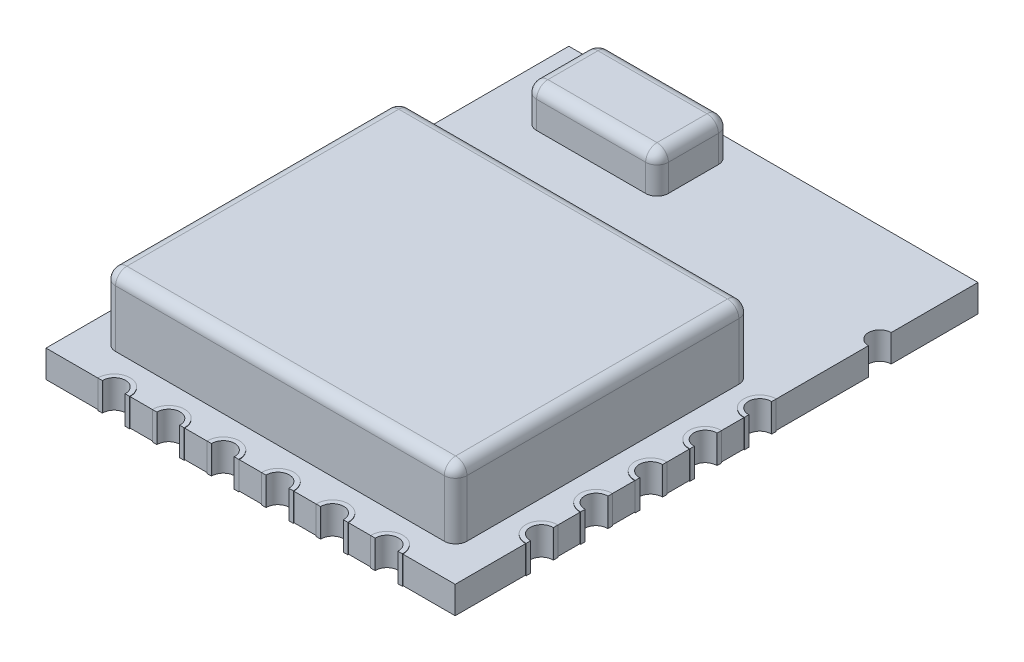
SolidWorks part; units mm, degrees
ref_plane "Front Plane" through (0, 0, 0) normal (0, 0, 1) x (1, 0, 0)
ref_plane "Top Plane" through (0, 0, 0) normal (0, 1, 0) x (1, 0, 0)
ref_plane "Right Plane" through (0, 0, 0) normal (1, 0, 0) x (0, 0, -1)
sketch "Sketch2" plane through (0, 0, 0) normal (0, 1, 0) x (1, 0, 0)
  line L0 (-4.5, -5.75) -> (-4.5, -4.1)
  line L3 (-4.5, 5.75) -> (4.5, 5.75)
  line L4 (4.5, -5.75) -> (4.5, -4.1)
  line L5 (-4.5, -5.75) -> (4.5, 5.75) construction
  line L6 (-4.5, 5.75) -> (4.5, -5.75) construction
  line L7 (0, -5.75) -> (0, 5.75) construction
  line L8 (-4.5, 1.2) -> (-4.5, 5.75)
  line L9 (-4.5, 0) -> (-4.5, 0.7)
  line L10 (-4.5, -1.2) -> (-4.5, -0.5)
  line L11 (-4.5, -2.4) -> (-4.5, -1.7)
  line L12 (-4.5, -2.9) -> (-4.5, -3.6)
  line L13 (4.5, 1.2) -> (4.5, 3.34)
  line L14 (4.5, 0) -> (4.5, 0.7)
  line L15 (4.5, -1.2) -> (4.5, -0.5)
  line L16 (4.5, -2.4) -> (4.5, -1.7)
  line L17 (4.5, -3.6) -> (4.5, -2.9)
  line L18 (-4.5, -5.75) -> (-3.25, -5.75)
  line L19 (-2.75, -5.75) -> (-2.05, -5.75)
  line L20 (-1.55, -5.75) -> (-0.85, -5.75)
  line L21 (-0.35, -5.75) -> (0.35, -5.75)
  line L22 (0.85, -5.75) -> (1.55, -5.75)
  line L23 (2.05, -5.75) -> (2.75, -5.75)
  line L24 (3.25, -5.75) -> (4.5, -5.75)
  line L25 (4.5, 3.84) -> (4.5, 5.75)
  arc A0 (-4.5, -4.1) -> (-4.5, -3.6) centre (-4.5, -3.85) ccw
  arc A1 (-4.5, -2.9) -> (-4.5, -2.4) centre (-4.5, -2.65) ccw
  arc A2 (-4.5, -1.7) -> (-4.5, -1.2) centre (-4.5, -1.45) ccw
  arc A3 (-4.5, -0.5) -> (-4.5, 0) centre (-4.5, -0.25) ccw
  arc A4 (-4.5, 0.7) -> (-4.5, 1.2) centre (-4.5, 0.95) ccw
  arc A5 (4.5, -4.1) -> (4.5, -3.6) centre (4.5, -3.85) cw
  arc A6 (4.5, -2.9) -> (4.5, -2.4) centre (4.5, -2.65) cw
  arc A7 (4.5, -1.7) -> (4.5, -1.2) centre (4.5, -1.45) cw
  arc A8 (4.5, -0.5) -> (4.5, 0) centre (4.5, -0.25) cw
  arc A9 (4.5, 0.7) -> (4.5, 1.2) centre (4.5, 0.95) cw
  arc A10 (-2.75, -5.75) -> (-3.25, -5.75) centre (-3, -5.75) ccw
  arc A11 (-1.55, -5.75) -> (-2.05, -5.75) centre (-1.8, -5.75) ccw
  arc A12 (-0.35, -5.75) -> (-0.85, -5.75) centre (-0.6, -5.75) ccw
  arc A13 (0.85, -5.75) -> (0.35, -5.75) centre (0.6, -5.75) ccw
  arc A14 (2.05, -5.75) -> (1.55, -5.75) centre (1.8, -5.75) ccw
  arc A15 (3.25, -5.75) -> (2.75, -5.75) centre (3, -5.75) ccw
  arc A16 (4.5, 3.84) -> (4.5, 3.34) centre (4.5, 3.59) ccw
  point P0 (0, 0)
  dimension "D1" = 0.25
  dimension "D2" = 4.5
  dimension "D3" = 0.95
  dimension "D4" = 3.59
  dimension "D5" = 5.75
extrude "Boss-Extrude1" add sketch "Sketch2" along normal blind 0.6 contours L3 L25 A16 L13 A9 L14 A8 L15 A7 L16 A6 L17 A5 L4 L24 A15 L23 A14 L22 A13 L21 A12 L20 A11 L19 A10 L18 L0 A0 L12 A1 L11 A2 L10 A3 L9 A4 L8
sketch "Sketch3" plane through (0, 0.6, 0) normal (0, 1, 0) x (1, 0, 0)
  line L0 (-4.5, 1.2) -> (-4.5, 5.75) construction
  line L2 (-3.92, -5.05) -> (3.81, -5.05)
  line L5 (-3.92, 1.43) -> (-3.92, -5.05)
  line L7 (3.81, 1.43) -> (3.81, -5.05)
  line L9 (3.81, 1.43) -> (-3.92, 1.43)
  dimension "D1" = 0.58
  dimension "D2" = 8.31
  dimension "D3" = 4.32
  dimension "D4" = 10.8
extrude "Boss-Extrude2" add sketch "Sketch3" along normal blind 1.5 contours L9 L5 L2 L7
fillet "Fillet1" radius 0.25 8 edges at (-0.055, 2.1, 5.05) (-3.92, 2.1, 1.81) (-0.055, 2.1, -1.43) (3.81, 2.1, 1.81) (3.81, 1.35, -1.43) (3.81, 1.35, 5.05) (-3.92, 1.35, 5.05) (-3.92, 1.35, -1.43)
sketch "Sketch4" plane through (0, 0.6, 0) normal (0, 1, 0) x (1, 0, 0)
  line L0 (-4.5, 1.2) -> (-4.5, 5.75) construction
  line L2 (-3.67, -5.05) -> (3.56, -5.05) construction
  line L3 (-3.5, 5.39) -> (-0.6, 5.39)
  line L5 (-3.5, 5.39) -> (-3.5, 3.79)
  line L6 (-3.5, 3.79) -> (-0.6, 3.79)
  line L7 (-0.6, 5.39) -> (-0.6, 3.79)
  dimension "D1" = 2.9
  dimension "D2" = 1.6
  dimension "D3" = 1
  dimension "D4" = 8.84
extrude "Boss-Extrude3" add sketch "Sketch4" along normal blind 0.8438 contours L3 L7 L6 L5
fillet "Fillet2" radius 0.25 8 edges at (-3.5, 1.0219, -5.39) (-3.5, 1.0219, -3.79) (-0.6, 1.0219, -5.39) (-0.6, 1.0219, -3.79) (-3.5, 1.4438, -4.59) (-2.05, 1.4438, -5.39) (-0.6, 1.4438, -4.59) (-2.05, 1.4438, -3.79)
sketch "Sketch6" plane through (0, 0, 0) normal (0, -1, 0) x (1, 0, 0)
  line L0 (-4.5, 4.2) -> (-4.5, 4.1)
  line L1 (-3.35, 5.75) -> (-3.25, 5.75)
  line L2 (4.5, 4.2) -> (4.5, 4.1)
  line L3 (-4.5, -0.6) -> (-4.5, -0.7)
  line L4 (-4.5, 0.6) -> (-4.5, 0.5)
  line L5 (-4.5, 1.8) -> (-4.5, 1.7)
  line L6 (-4.5, 3) -> (-4.5, 2.9)
  line L7 (-4.5, 3.6) -> (-4.5, 3.5)
  line L8 (-4.5, 2.4) -> (-4.5, 2.3)
  line L9 (-4.5, 1.2) -> (-4.5, 1.1)
  line L10 (-4.5, 0) -> (-4.5, -0.1)
  line L11 (-4.5, -1.2) -> (-4.5, -1.3)
  line L12 (-2.75, 5.75) -> (-2.65, 5.75)
  line L13 (-1.55, 5.75) -> (-1.45, 5.75)
  line L14 (-0.35, 5.75) -> (-0.25, 5.75)
  line L15 (0.85, 5.75) -> (0.95, 5.75)
  line L16 (2.05, 5.75) -> (2.15, 5.75)
  line L17 (3.25, 5.75) -> (3.35, 5.75)
  line L18 (4.5, 3.6) -> (4.5, 3.5)
  line L19 (4.5, 2.4) -> (4.5, 2.3)
  line L20 (4.5, 1.2) -> (4.5, 1.1)
  line L21 (4.5, 0) -> (4.5, -0.1)
  line L22 (4.5, -1.2) -> (4.5, -1.3)
  line L23 (4.5, -0.6) -> (4.5, -0.7)
  line L24 (4.5, 0.6) -> (4.5, 0.5)
  line L25 (4.5, 1.8) -> (4.5, 1.7)
  line L26 (4.5, 3) -> (4.5, 2.9)
  line L27 (2.65, 5.75) -> (2.75, 5.75)
  line L28 (1.45, 5.75) -> (1.55, 5.75)
  line L29 (0.25, 5.75) -> (0.35, 5.75)
  line L30 (-0.95, 5.75) -> (-0.85, 5.75)
  line L31 (-2.15, 5.75) -> (-2.05, 5.75)
  line L32 (-4.5, -1.2) -> (-4.5, -5.75) construction
  line L33 (-4.5, -5.75) -> (4.5, -5.75) construction
  arc A0 (-4.5, 3.5) -> (-4.5, 4.2) centre (-4.5, 3.85) ccw
  arc A1 (-4.5, 2.3) -> (-4.5, 3) centre (-4.5, 2.65) ccw
  arc A2 (-4.5, 1.1) -> (-4.5, 1.8) centre (-4.5, 1.45) ccw
  arc A3 (-4.5, -0.1) -> (-4.5, 0.6) centre (-4.5, 0.25) ccw
  arc A4 (-4.5, -1.3) -> (-4.5, -0.6) centre (-4.5, -0.95) ccw
  arc A5 (-3.35, 5.75) -> (-2.65, 5.75) centre (-3, 5.75) ccw
  arc A6 (-2.15, 5.75) -> (-1.45, 5.75) centre (-1.8, 5.75) ccw
  arc A7 (-0.95, 5.75) -> (-0.25, 5.75) centre (-0.6, 5.75) ccw
  arc A8 (0.25, 5.75) -> (0.95, 5.75) centre (0.6, 5.75) ccw
  arc A9 (1.45, 5.75) -> (2.15, 5.75) centre (1.8, 5.75) ccw
  arc A10 (2.65, 5.75) -> (3.35, 5.75) centre (3, 5.75) ccw
  arc A11 (4.5, 4.2) -> (4.5, 3.5) centre (4.5, 3.85) ccw
  arc A12 (4.5, 3) -> (4.5, 2.3) centre (4.5, 2.65) ccw
  arc A13 (4.5, 1.8) -> (4.5, 1.1) centre (4.5, 1.45) ccw
  arc A14 (4.5, 0.6) -> (4.5, -0.1) centre (4.5, 0.25) ccw
  arc A15 (4.5, -0.6) -> (4.5, -1.3) centre (4.5, -0.95) ccw
  arc A16 (4.5, -0.7) -> (4.5, -1.2) centre (4.5, -0.95) ccw
  arc A17 (-4.5, 3.6) -> (-4.5, 4.1) centre (-4.5, 3.85) ccw
  arc A18 (-4.5, 2.4) -> (-4.5, 2.9) centre (-4.5, 2.65) ccw
  arc A19 (-4.5, 1.2) -> (-4.5, 1.7) centre (-4.5, 1.45) ccw
  arc A20 (-4.5, 0) -> (-4.5, 0.5) centre (-4.5, 0.25) ccw
  arc A21 (-4.5, -1.2) -> (-4.5, -0.7) centre (-4.5, -0.95) ccw
  arc A22 (-3.25, 5.75) -> (-2.75, 5.75) centre (-3, 5.75) ccw
  arc A23 (-2.05, 5.75) -> (-1.55, 5.75) centre (-1.8, 5.75) ccw
  arc A24 (-0.85, 5.75) -> (-0.35, 5.75) centre (-0.6, 5.75) ccw
  arc A25 (0.35, 5.75) -> (0.85, 5.75) centre (0.6, 5.75) ccw
  arc A26 (1.55, 5.75) -> (2.05, 5.75) centre (1.8, 5.75) ccw
  arc A27 (2.75, 5.75) -> (3.25, 5.75) centre (3, 5.75) ccw
  arc A28 (4.5, 4.1) -> (4.5, 3.6) centre (4.5, 3.85) ccw
  arc A29 (4.5, 2.9) -> (4.5, 2.4) centre (4.5, 2.65) ccw
  arc A30 (4.5, 1.7) -> (4.5, 1.2) centre (4.5, 1.45) ccw
  arc A31 (4.5, 0.5) -> (4.5, 0) centre (4.5, 0.25) ccw
  line M10 (-4.5, -1.2) -> (-4.5, -5.75)
  line M14 (4.5, -3.34) -> (4.5, -1.2)
  arc M15 (4.5, -1.2) -> (4.5, -0.7) centre (4.5, -0.95) cw
  line M16 (4.5, -0.7) -> (4.5, 0)
  arc M17 (4.5, 0) -> (4.5, 0.5) centre (4.5, 0.25) cw
  line M18 (4.5, 0.5) -> (4.5, 1.2)
  arc M19 (4.5, 1.2) -> (4.5, 1.7) centre (4.5, 1.45) cw
  line M20 (4.5, 1.7) -> (4.5, 2.4)
  arc M21 (4.5, 2.4) -> (4.5, 2.9) centre (4.5, 2.65) cw
  line M22 (4.5, 2.9) -> (4.5, 3.6)
  arc M23 (4.5, 3.6) -> (4.5, 4.1) centre (4.5, 3.85) cw
  line M24 (4.5, 4.1) -> (4.5, 5.75)
  line M25 (4.5, 5.75) -> (3.25, 5.75)
  arc M26 (3.25, 5.75) -> (2.75, 5.75) centre (3, 5.75) cw
  line M27 (2.75, 5.75) -> (2.05, 5.75)
  arc M28 (2.05, 5.75) -> (1.55, 5.75) centre (1.8, 5.75) cw
  line M29 (1.55, 5.75) -> (0.85, 5.75)
  arc M30 (0.85, 5.75) -> (0.35, 5.75) centre (0.6, 5.75) cw
  line M31 (0.35, 5.75) -> (-0.35, 5.75)
  arc M32 (-0.35, 5.75) -> (-0.85, 5.75) centre (-0.6, 5.75) cw
  line M33 (-0.85, 5.75) -> (-1.55, 5.75)
  arc M34 (-1.55, 5.75) -> (-2.05, 5.75) centre (-1.8, 5.75) cw
  line M35 (-2.05, 5.75) -> (-2.75, 5.75)
  arc M36 (-2.75, 5.75) -> (-3.25, 5.75) centre (-3, 5.75) cw
  line M37 (-3.25, 5.75) -> (-4.5, 5.75)
  line M46 (-4.5, 0) -> (-4.5, -0.7)
  arc M47 (-4.5, -0.7) -> (-4.5, -1.2) centre (-4.5, -0.95) cw
  dimension "D1" = 0.35
  dimension "D2" = 0.25
  dimension "D3" = 1.5
  dimension "D4" = 2.7
  dimension "D5" = 3.9
  dimension "D6" = 5.1
  dimension "D7" = 6.3
  dimension "D8" = 7.5
  dimension "D9" = 9
  dimension "D10" = 4.8
  dimension "D11" = 6
  dimension "D12" = 7.2
  dimension "D13" = 8.4
  dimension "D14" = 9.6
  dimension "D15" = 11.5
extrude "Boss-Extrude4" add sketch "Sketch6" against normal blind 0.61 and the other way blind 0.01 contours A4 M10 M46 M47 | A5 M37 M35 M36 | A6 M35 M33 M34 | A7 M33 M31 M32 | A8 M31 M29 M30 | A9 M29 M27 M28 | A10 M27 M25 M26 | A11 M24 M22 M23 | A12 M22 M20 M21 | A13 M20 M18 M19 | A14 M18 M16 M17 | A15 M16 M14 M15 | A17 L0 A0 L7 | A18 L6 A1 L8 | A2 L5 A19 L9 | A20 L4 A3 L10
sketch "Sketch7" plane through (0, 0, 0) normal (0, -1, 0) x (1, 0, 0)
  line L0 (-4.5, 2.3) -> (-3.5, 2.3)
  line L1 (-4.5, 3.5) -> (-3.5, 3.5)
  line L2 (-4.5, 3.5) -> (-4.5, 3.6)
  line L3 (-4.5, 4.2) -> (-3.5, 4.2)
  line L4 (-3.5, 3.5) -> (-3.5, 4.2)
  line L5 (-4.5, 3) -> (-3.5, 3)
  line L6 (-4.5, 2.3) -> (-4.5, 2.4)
  line L7 (-3.5, 2.3) -> (-3.5, 3)
  line L8 (-4.5, 1.1) -> (-3.5, 1.1)
  line L9 (-4.5, 1.8) -> (-3.5, 1.8)
  line L10 (-4.5, 1.1) -> (-4.5, 1.2)
  line L11 (-3.5, 1.1) -> (-3.5, 1.8)
  line L12 (-4.5, -0.1) -> (-3.5, -0.1)
  line L13 (-4.5, 0.6) -> (-3.5, 0.6)
  line L14 (-4.5, -0.1) -> (-4.5, 0)
  line L15 (-3.5, -0.1) -> (-3.5, 0.6)
  line L16 (-4.5, -1.3) -> (-3.5, -1.3)
  line L17 (-4.5, -0.6) -> (-3.5, -0.6)
  line L18 (-4.5, -1.3) -> (-4.5, -1.2)
  line L19 (-3.5, -1.3) -> (-3.5, -0.6)
  line L20 (-4.5, 4.1) -> (-4.5, 4.2)
  line L23 (3.5, -1.3) -> (3.5, -0.6)
  line L24 (4.5, -1.3) -> (4.5, -1.2)
  line L25 (4.5, -0.6) -> (3.5, -0.6)
  line L26 (4.5, -1.3) -> (3.5, -1.3)
  line L27 (3.5, -0.1) -> (3.5, 0.6)
  line L28 (4.5, -0.1) -> (4.5, 0)
  line L29 (4.5, 0.6) -> (3.5, 0.6)
  line L30 (4.5, -0.1) -> (3.5, -0.1)
  line L31 (3.5, 1.1) -> (3.5, 1.8)
  line L32 (4.5, 1.1) -> (4.5, 1.2)
  line L33 (4.5, 1.8) -> (3.5, 1.8)
  line L34 (4.5, 1.1) -> (3.5, 1.1)
  line L35 (3.5, 2.3) -> (3.5, 3)
  line L36 (4.5, 2.3) -> (4.5, 2.4)
  line L37 (4.5, 3) -> (3.5, 3)
  line L38 (3.5, 3.5) -> (3.5, 4.2)
  line L39 (4.5, 4.2) -> (3.5, 4.2)
  line L40 (4.5, 3.5) -> (4.5, 3.6)
  line L41 (4.5, 3.5) -> (3.5, 3.5)
  line L42 (4.5, 2.3) -> (3.5, 2.3)
  line L43 (-2.15, 5.75) -> (-2.05, 5.75)
  line L44 (-3.35, 5.75) -> (-3.25, 5.75)
  line L45 (-3.35, 5.75) -> (-3.35, 4.75)
  line L46 (-3.35, 4.75) -> (-2.65, 4.75)
  line L47 (-2.65, 5.75) -> (-2.65, 4.75)
  line L48 (-2.15, 5.75) -> (-2.15, 4.75)
  line L49 (-2.15, 4.75) -> (-1.45, 4.75)
  line L50 (-1.45, 5.75) -> (-1.45, 4.75)
  line L51 (-0.95, 5.75) -> (-0.85, 5.75)
  line L52 (-0.95, 5.75) -> (-0.95, 4.75)
  line L53 (-0.95, 4.75) -> (-0.25, 4.75)
  line L54 (-0.25, 5.75) -> (-0.25, 4.75)
  line L55 (0.25, 5.75) -> (0.35, 5.75)
  line L56 (0.25, 5.75) -> (0.25, 4.75)
  line L57 (0.25, 4.75) -> (0.95, 4.75)
  line L58 (0.95, 5.75) -> (0.95, 4.75)
  line L59 (1.45, 5.75) -> (1.55, 5.75)
  line L60 (1.45, 5.75) -> (1.45, 4.75)
  line L61 (1.45, 4.75) -> (2.15, 4.75)
  line L62 (2.15, 5.75) -> (2.15, 4.75)
  line L63 (2.65, 5.75) -> (2.75, 5.75)
  line L64 (2.65, 5.75) -> (2.65, 4.75)
  line L65 (2.65, 4.75) -> (3.35, 4.75)
  line L66 (3.35, 5.75) -> (3.35, 4.75)
  line L67 (-4.5, 2.9) -> (-4.5, 3)
  line L68 (-4.5, 1.7) -> (-4.5, 1.8)
  line L69 (-4.5, 0.5) -> (-4.5, 0.6)
  line L70 (-4.5, -0.7) -> (-4.5, -0.6)
  line L71 (-2.75, 5.75) -> (-2.65, 5.75)
  line L72 (-1.55, 5.75) -> (-1.45, 5.75)
  line L73 (-0.35, 5.75) -> (-0.25, 5.75)
  line L74 (0.85, 5.75) -> (0.95, 5.75)
  line L75 (2.05, 5.75) -> (2.15, 5.75)
  line L76 (3.25, 5.75) -> (3.35, 5.75)
  line L77 (4.5, 4.1) -> (4.5, 4.2)
  line L78 (4.5, 2.9) -> (4.5, 3)
  line L79 (4.5, 1.7) -> (4.5, 1.8)
  line L80 (4.5, 0.5) -> (4.5, 0.6)
  line L81 (4.5, -0.7) -> (4.5, -0.6)
  line L82 (-4.5, 5.75) -> (-4.5, 4.2) construction
  line L83 (-4.5, 5.75) -> (-3.35, 5.75) construction
  arc A0 (-3.25, 5.75) -> (-2.75, 5.75) centre (-3, 5.75) ccw
  arc A1 (-2.05, 5.75) -> (-1.55, 5.75) centre (-1.8, 5.75) ccw
  arc A2 (-0.85, 5.75) -> (-0.35, 5.75) centre (-0.6, 5.75) ccw
  arc A3 (0.35, 5.75) -> (0.85, 5.75) centre (0.6, 5.75) ccw
  arc A4 (1.55, 5.75) -> (2.05, 5.75) centre (1.8, 5.75) ccw
  arc A5 (2.75, 5.75) -> (3.25, 5.75) centre (3, 5.75) ccw
  arc A6 (-4.5, 3.6) -> (-4.5, 4.1) centre (-4.5, 3.85) ccw
  arc A7 (-4.5, 2.4) -> (-4.5, 2.9) centre (-4.5, 2.65) ccw
  arc A8 (-4.5, 1.2) -> (-4.5, 1.7) centre (-4.5, 1.45) ccw
  arc A9 (-4.5, 0) -> (-4.5, 0.5) centre (-4.5, 0.25) ccw
  arc A10 (-4.5, -1.2) -> (-4.5, -0.7) centre (-4.5, -0.95) ccw
  arc A11 (4.5, -0.7) -> (4.5, -1.2) centre (4.5, -0.95) ccw
  arc A12 (4.5, 0.5) -> (4.5, 0) centre (4.5, 0.25) ccw
  arc A13 (4.5, 1.7) -> (4.5, 1.2) centre (4.5, 1.45) ccw
  arc A14 (4.5, 2.9) -> (4.5, 2.4) centre (4.5, 2.65) ccw
  arc A15 (4.5, 4.1) -> (4.5, 3.6) centre (4.5, 3.85) ccw
  dimension "D1" = 1
extrude "Boss-Extrude5" add sketch "Sketch7" along normal blind 0.01 contours L46 L47 L71 A0 L44 L45
sketch "Sketch8" plane through (4.5, 0, 0) normal (1, 0, 0) x (0, 0, -1)
  line L0 (-3.6, 0.61) -> (-3.6, -0.01)
  line L1 (-4.2, 0.61) -> (-4.1, 0.61)
  line L2 (-4.2, 0.61) -> (-4.2, -0.01)
  line L3 (-4.2, -0.01) -> (-4.1, -0.01)
  line L4 (-4.1, 0.61) -> (-4.1, -0.01)
  line L5 (-3.6, 0.61) -> (-3.5, 0.61)
  line L6 (-3.6, -0.01) -> (-3.5, -0.01)
  line L7 (-3.5, 0.61) -> (-3.5, -0.01)
  line L8 (-3, 0.61) -> (-3, -0.01)
  line L9 (-3, 0.61) -> (-2.9, 0.61)
  line L10 (-3, -0.01) -> (-2.9, -0.01)
  line L11 (-2.9, 0.61) -> (-2.9, -0.01)
  line L12 (-2.4, 0.61) -> (-2.4, -0.01)
  line L13 (-2.4, 0.61) -> (-2.3, 0.61)
  line L14 (-2.4, -0.01) -> (-2.3, -0.01)
  line L15 (-2.3, 0.61) -> (-2.3, -0.01)
  line L16 (-1.8, 0.61) -> (-1.8, -0.01)
  line L17 (-1.8, 0.61) -> (-1.7, 0.61)
  line L18 (-1.8, -0.01) -> (-1.7, -0.01)
  line L19 (-1.7, 0.61) -> (-1.7, -0.01)
  line L20 (-1.2, 0.61) -> (-1.2, -0.01)
  line L21 (-1.2, 0.61) -> (-1.1, 0.61)
  line L22 (-1.2, -0.01) -> (-1.1, -0.01)
  line L23 (-1.1, 0.61) -> (-1.1, -0.01)
  line L24 (-0.6, 0.61) -> (-0.6, -0.01)
  line L25 (-0.6, 0.61) -> (-0.5, 0.61)
  line L26 (-0.6, -0.01) -> (-0.5, -0.01)
  line L27 (-0.5, 0.61) -> (-0.5, -0.01)
  line L28 (0, 0.61) -> (0, -0.01)
  line L29 (0, 0.61) -> (0.1, 0.61)
  line L30 (0, -0.01) -> (0.1, -0.01)
  line L31 (0.1, 0.61) -> (0.1, -0.01)
  line L32 (0.6, 0.61) -> (0.6, -0.01)
  line L33 (0.6, 0.61) -> (0.7, 0.61)
  line L34 (0.6, -0.01) -> (0.7, -0.01)
  line L35 (0.7, 0.61) -> (0.7, -0.01)
  line L36 (1.2, 0.61) -> (1.2, -0.01)
  line L37 (1.2, 0.61) -> (1.3, 0.61)
  line L38 (1.2, -0.01) -> (1.3, -0.01)
  line L39 (1.3, 0.61) -> (1.3, -0.01)
  line L40 (-4.1, 0.61) -> (-4.1, -0.01) construction
  line L41 (-4.1, 0.61) -> (-4.2, 0.61) construction
  dimension "D1" = 0.5
  dimension "D2" = 0.6
  dimension "D3" = 1.1
  dimension "D4" = 1.7
  dimension "D5" = 2.3
  dimension "D6" = 2.9
  dimension "D7" = 3.5
  dimension "D8" = 4.1
  dimension "D9" = 4.7
  dimension "D10" = 5.3
  dimension "D11" = 0.62
sketch "Sketch9" plane through (0, 0, 5.75) normal (0, 0, 1) x (1, 0, 0)
  line L0 (-2.65, 0.61) -> (-2.65, -0.01)
  line L1 (-3.35, 0.61) -> (-3.25, 0.61)
  line L2 (-3.35, 0.61) -> (-3.35, -0.01)
  line L3 (-3.35, -0.01) -> (-3.25, -0.01)
  line L4 (-3.25, 0.61) -> (-3.25, -0.01)
  line L5 (-2.75, 0.61) -> (-2.65, 0.61)
  line L6 (-2.75, -0.01) -> (-2.65, -0.01)
  line L7 (-2.75, 0.61) -> (-2.75, -0.01)
  line L8 (-2.05, 0.61) -> (-2.05, -0.01)
  line L9 (-2.15, 0.61) -> (-2.05, 0.61)
  line L10 (-2.15, -0.01) -> (-2.05, -0.01)
  line L11 (-2.15, 0.61) -> (-2.15, -0.01)
  line L12 (-1.45, 0.61) -> (-1.45, -0.01)
  line L13 (-1.55, 0.61) -> (-1.45, 0.61)
  line L14 (-1.55, -0.01) -> (-1.45, -0.01)
  line L15 (-1.55, 0.61) -> (-1.55, -0.01)
  line L16 (-0.85, 0.61) -> (-0.85, -0.01)
  line L17 (-0.95, 0.61) -> (-0.85, 0.61)
  line L18 (-0.95, -0.01) -> (-0.85, -0.01)
  line L19 (-0.95, 0.61) -> (-0.95, -0.01)
  line L20 (-0.25, 0.61) -> (-0.25, -0.01)
  line L21 (-0.35, 0.61) -> (-0.25, 0.61)
  line L22 (-0.35, -0.01) -> (-0.25, -0.01)
  line L23 (-0.35, 0.61) -> (-0.35, -0.01)
  line L24 (0.25, 0.61) -> (0.35, 0.61)
  line L25 (0.35, 0.61) -> (0.35, -0.01)
  line L26 (0.25, -0.01) -> (0.35, -0.01)
  line L27 (0.25, 0.61) -> (0.25, -0.01)
  line L28 (0.85, 0.61) -> (0.95, 0.61)
  line L29 (0.95, 0.61) -> (0.95, -0.01)
  line L30 (0.85, -0.01) -> (0.95, -0.01)
  line L31 (0.85, 0.61) -> (0.85, -0.01)
  line L32 (1.45, 0.61) -> (1.55, 0.61)
  line L33 (1.55, 0.61) -> (1.55, -0.01)
  line L34 (1.45, -0.01) -> (1.55, -0.01)
  line L35 (1.45, 0.61) -> (1.45, -0.01)
  line L36 (2.05, 0.61) -> (2.15, 0.61)
  line L37 (2.15, 0.61) -> (2.15, -0.01)
  line L38 (2.05, -0.01) -> (2.15, -0.01)
  line L39 (2.05, 0.61) -> (2.05, -0.01)
  line L40 (2.65, 0.61) -> (2.75, 0.61)
  line L41 (2.75, 0.61) -> (2.75, -0.01)
  line L42 (2.65, -0.01) -> (2.75, -0.01)
  line L43 (2.65, 0.61) -> (2.65, -0.01)
  line L44 (3.25, 0.61) -> (3.35, 0.61)
  line L45 (3.35, 0.61) -> (3.35, -0.01)
  line L46 (3.25, -0.01) -> (3.35, -0.01)
  line L47 (3.25, 0.61) -> (3.25, -0.01)
  line L48 (-3.35, 0.6) -> (-3.35, 0.61) construction
  line L49 (-3.25, 0.61) -> (-3.35, 0.61) construction
  dimension "D1" = 0.1
  dimension "D2" = 0.6
  dimension "D3" = 1.2
  dimension "D4" = 1.8
  dimension "D5" = 2.4
  dimension "D6" = 3
  dimension "D7" = 3.6
  dimension "D8" = 4.2
  dimension "D9" = 4.8
  dimension "D10" = 5.4
  dimension "D11" = 6
  dimension "D12" = 6.6
  dimension "D13" = 0.62
sketch "Sketch10" plane through (-4.5, 0, 0) normal (-1, 0, 0) x (0, 0, 1)
  line L0 (-0.7, 0.61) -> (-0.6, 0.61)
  line L1 (-1.3, 0.61) -> (-1.2, 0.61)
  line L2 (-1.3, 0.61) -> (-1.3, -0.01)
  line L3 (-1.3, -0.01) -> (-1.2, -0.01)
  line L4 (-1.2, 0.61) -> (-1.2, -0.01)
  line L5 (-0.6, 0.61) -> (-0.6, -0.01)
  line L6 (-0.7, -0.01) -> (-0.6, -0.01)
  line L7 (-0.7, 0.61) -> (-0.7, -0.01)
  line L8 (-0.1, 0.61) -> (0, 0.61)
  line L9 (0, 0.61) -> (0, -0.01)
  line L10 (-0.1, -0.01) -> (0, -0.01)
  line L11 (-0.1, 0.61) -> (-0.1, -0.01)
  line L12 (0.5, 0.61) -> (0.6, 0.61)
  line L13 (0.6, 0.61) -> (0.6, -0.01)
  line L14 (0.5, -0.01) -> (0.6, -0.01)
  line L15 (0.5, 0.61) -> (0.5, -0.01)
  line L16 (1.1, 0.61) -> (1.2, 0.61)
  line L17 (1.2, 0.61) -> (1.2, -0.01)
  line L18 (1.1, -0.01) -> (1.2, -0.01)
  line L19 (1.1, 0.61) -> (1.1, -0.01)
  line L20 (1.7, 0.61) -> (1.8, 0.61)
  line L21 (1.8, 0.61) -> (1.8, -0.01)
  line L22 (1.7, -0.01) -> (1.8, -0.01)
  line L23 (1.7, 0.61) -> (1.7, -0.01)
  line L24 (2.3, 0.61) -> (2.4, 0.61)
  line L25 (2.4, 0.61) -> (2.4, -0.01)
  line L26 (2.3, -0.01) -> (2.4, -0.01)
  line L27 (2.3, 0.61) -> (2.3, -0.01)
  line L28 (2.9, 0.61) -> (3, 0.61)
  line L29 (3, 0.61) -> (3, -0.01)
  line L30 (2.9, -0.01) -> (3, -0.01)
  line L31 (2.9, 0.61) -> (2.9, -0.01)
  line L32 (3.5, 0.61) -> (3.6, 0.61)
  line L33 (3.6, 0.61) -> (3.6, -0.01)
  line L34 (3.5, -0.01) -> (3.6, -0.01)
  line L35 (3.5, 0.61) -> (3.5, -0.01)
  line L36 (4.1, 0.61) -> (4.2, 0.61)
  line L37 (4.2, 0.61) -> (4.2, -0.01)
  line L38 (4.1, -0.01) -> (4.2, -0.01)
  line L39 (4.1, 0.61) -> (4.1, -0.01)
  line L40 (-1.2, 0.61) -> (-1.2, -0.01) construction
  line L41 (-1.2, 0.61) -> (-1.3, 0.61) construction
  dimension "D1" = 0.5
  dimension "D2" = 0.6
  dimension "D3" = 1.1
  dimension "D4" = 1.7
  dimension "D5" = 2.3
  dimension "D6" = 2.9
  dimension "D7" = 3.5
  dimension "D8" = 4.1
  dimension "D9" = 4.7
  dimension "D10" = 5.3
  dimension "D11" = 0.62
extrude "Boss-Extrude6" add sketch "Sketch8" along normal blind 0.01
extrude "Boss-Extrude7" add sketch "Sketch10" along normal blind 0.01
extrude "Boss-Extrude8" add sketch "Sketch9" along normal blind 0.01
